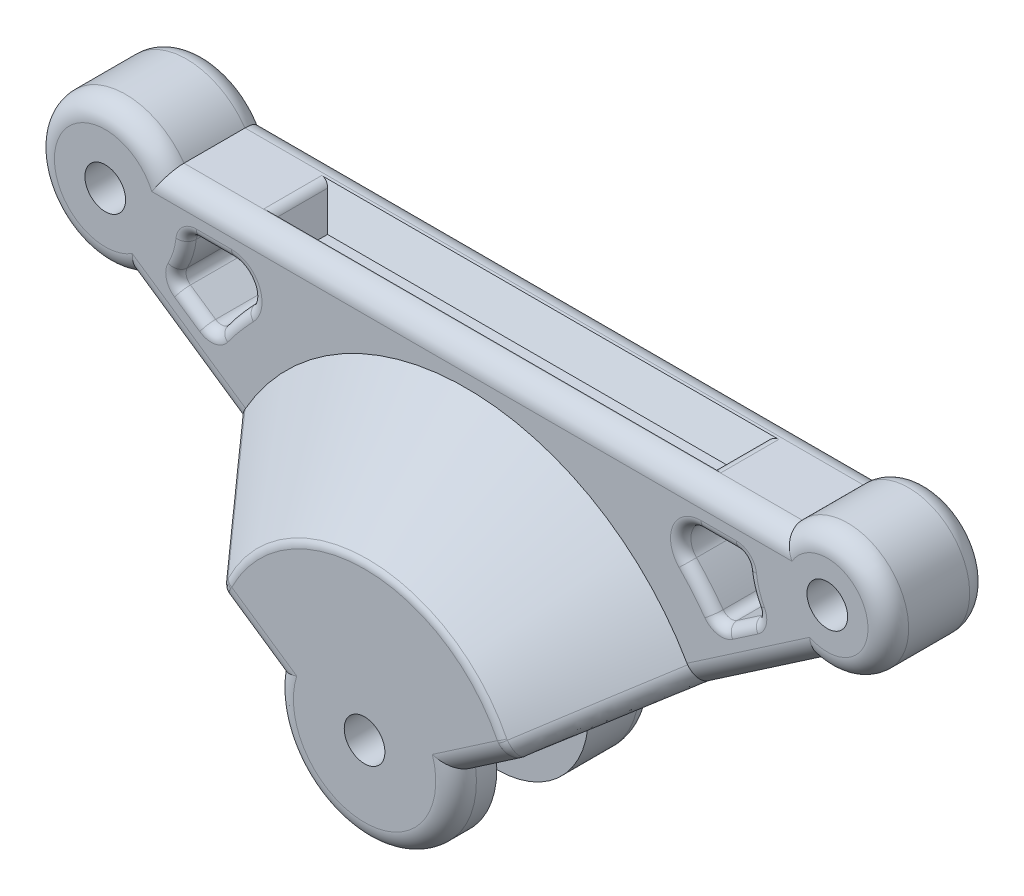
SolidWorks part; units mm, degrees
ref_plane "前视基准面" through (0, 0, 0) normal (0, 0, 1) x (1, 0, 0)
ref_plane "上视基准面" through (0, 0, 0) normal (0, 1, 0) x (1, 0, 0)
ref_plane "右视基准面" through (0, 0, 0) normal (1, 0, 0) x (0, 0, -1)
sketch "草图2" plane through (0, 0, 0) normal (0, 0, 1) x (1, 0, 0)
  line L0 (8.9132, 1.2471) -> (34.065, 18.4383)
  line L1 (31.0279, 28.2642) -> (-29.7554, 28.2642)
  line L2 (-33.0145, 17.7203) -> (-8.9132, 1.2471)
  arc A0 (-8.9132, 1.2471) -> (8.9132, 1.2471) centre (0, 0) ccw
  arc A1 (34.065, 18.4383) -> (31.0279, 28.2642) centre (35.5, 24.2642) ccw
  arc A2 (-29.7554, 28.2642) -> (-33.0145, 17.7203) centre (-35.5, 24.2642) ccw
  point P9 (-34.6477, 9.4763)
  point P10 (0, 0)
  dimension "D1" = 6
  dimension "D2" = 7
  dimension "D9" = 9
  dimension "D3" = 27.0171
  dimension "D4" = 60.7833
  dimension "D5" = 30.4656
  dimension "D6" = 29.1932
  dimension "D7" = 35.5
  dimension "D8" = 71
  dimension "D10" = 17.8264
extrude "凸台-拉伸1" add sketch "草图2" along normal blind 10
sketch "草图3" plane through (0, 0, 10) normal (0, 0, 1) x (1, 0, 0)
  line L0 (-8.9132, 1.2471) -> (-10.7168, 2.4799)
  line L1 (-33.0145, 17.7203) -> (-8.9132, 1.2471) construction
  line L2 (8.9132, 1.2471) -> (10.7168, 2.4799)
  line L3 (8.9132, 1.2471) -> (34.065, 18.4383) construction
  arc A0 (-8.9132, 1.2471) -> (8.9132, 1.2471) centre (0, 0) ccw construction
  arc A1 (-8.9132, 1.2471) -> (8.9132, 1.2471) centre (0, 0) ccw
  arc A2 (10.7168, 2.4799) -> (-10.7168, 2.4799) centre (0, 0) ccw
extrude "切除-拉伸1" cut sketch "草图3" against normal blind 3
sketch "草图4" plane through (0, 0, 10) normal (0, 0, 1) x (1, 0, 0)
  line L0 (10.7168, 2.4799) -> (34.065, 18.4383) construction
  line L1 (-33.0145, 17.7203) -> (-10.7168, 2.4799) construction
  line L2 (10.7168, 2.4799) -> (22.6308, 10.623)
  line L3 (-22.6308, 10.623) -> (-10.7168, 2.4799)
  arc A0 (22.6308, 10.623) -> (-22.6308, 10.623) centre (0, 0) ccw
  arc A1 (10.7168, 2.4799) -> (-10.7168, 2.4799) centre (0, 0) ccw construction
  arc A2 (10.7168, 2.4799) -> (-10.7168, 2.4799) centre (0, 0) ccw
extrude "凸台-拉伸2" add sketch "草图4" along normal blind 6
sketch "草图5" plane through (0, 0, 16) normal (0, 0, 1) x (1, 0, 0)
  line L0 (-10.7168, 2.4799) -> (-8.9132, 1.2471)
  line L1 (10.7168, 2.4799) -> (8.9132, 1.2471)
  line L2 (10.7168, 2.4799) -> (22.6308, 10.623)
  line L3 (-22.6308, 10.623) -> (-10.7168, 2.4799)
  line L4 (10.7168, 2.4799) -> (22.6308, 10.623)
  line L5 (-22.6308, 10.623) -> (-10.7168, 2.4799)
  arc A0 (-8.9132, 1.2471) -> (8.9132, 1.2471) centre (0, 0) ccw
  arc A2 (10.7168, 2.4799) -> (-10.7168, 2.4799) centre (0, 0) ccw
  arc A3 (22.6308, 10.623) -> (-22.6308, 10.623) centre (0, 0) ccw
  arc A5 (22.6308, 10.623) -> (-22.6308, 10.623) centre (0, 0) ccw
  dimension "D1" = 0
extrude "凸台-拉伸3" add sketch "草图5" along normal blind 4
sketch "草图6" plane through (0, 0, 0) normal (0, 0, -1) x (-1, 0, 0)
  line L0 (-28.8932, 19.7484) -> (-24.8254, 16.9681)
  line L1 (-23.0827, 24.2642) -> (-27.4968, 24.2642)
  line L2 (-31.0279, 28.2642) -> (29.7554, 28.2642) construction
  line L3 (-8.9132, 1.2471) -> (-34.065, 18.4383) construction
  line L4 (0.001, 0) -> (0.001, 28.2714) construction
  line L5 (23.0848, 24.2642) -> (27.4989, 24.2642)
  line L6 (28.8953, 19.7484) -> (24.8275, 16.9681)
  arc A0 (-24.8254, 16.9681) -> (-21.6432, 20.8757) centre (0.001, 0) cw
  arc A1 (-21.6432, 20.8757) -> (-23.0827, 24.2642) centre (-23.0827, 22.2642) ccw
  arc A2 (-27.4968, 24.2642) -> (-28.8932, 19.7484) centre (-35.4968, 24.2642) cw
  arc A3 (27.4989, 24.2642) -> (28.8953, 19.7484) centre (35.4989, 24.2642) ccw
  arc A4 (21.6453, 20.8757) -> (23.0848, 24.2642) centre (23.0848, 22.2642) cw
  arc A5 (24.8275, 16.9681) -> (21.6453, 20.8757) centre (0.001, 0) ccw
  dimension "D1" = 30.0711
  dimension "D2" = 2
  dimension "D3" = 8
  dimension "D6" = 12.73
  dimension "D4" = 4
  dimension "D5" = 4
  dimension "D7" = 15.9122
  dimension "D8" = 19.98
extrude "切除-拉伸2" cut sketch "草图6" against normal through all
draft "拔模1" type of draft neutral plane draft angle 45 faces to draft 1 face at (0, 17.8115, 15) neutral plane through (0, 0, 10) neutral plane normal (0, 0, 1) parameters "D1"=45
sketch "草图7" plane through (0, 28.2642, 0) normal (0, 1, 0) x (1, 0, 0)
  line L0 (-21.3644, -2.2763) -> (-21.3644, -7.9547)
  line L1 (-21.3644, -7.9547) -> (22.4255, -7.9547)
  line L2 (22.4255, -7.9547) -> (22.4255, -2.2763)
  line L3 (22.4255, -2.2763) -> (-21.3644, -2.2763)
extrude "切除-拉伸3" cut sketch "草图7" against normal blind 3 draft 30
sketch "草图8" plane through (0, 0, 0) normal (0, 0, -1) x (-1, 0, 0)
  circle A0 centre (0, 0) radius 2
  circle A5 centre (35.5, 24.2642) radius 2
  circle A6 centre (-35.5, 24.2642) radius 2
extrude "切除-拉伸4" cut sketch "草图8" against normal through all both and the other way through all
fillet "圆角1" radius 2 16 edges at (41.2324, 26.036, 0) (41.2324, 26.036, 10) (28.3479, 14.5307, 10) (11.5528, 3.0512, 20) (0, -9, 20) (-11.5528, 3.0512, 20) (-27.8226, 14.1716, 10) (-42.1878, 26.3314, 0) (-42.1878, 26.3314, 10) (0.6362, 28.2642, 10) (0.6362, 28.2642, 0) (0, -9, 0) (-20.9639, 9.4837, 0) (21.4891, 9.8427, 0)
fillet "圆角2" radius 1 5 edges at (13.9736, 5.4949, 19.4769) (-13.9736, 5.4949, 19.4769) (0, 15, 20)
fillet "圆角3" radius 1 28 edges at (27.8539, 21.9008, 0) (27.8539, 21.9008, 10) (26.8593, 18.3583, 0) (28.8932, 19.7484, 5) (26.8593, 18.3583, 10) (23.3163, 18.9887, 0) (24.8254, 16.9681, 5) (23.3163, 18.9887, 10) (-25.2919, 24.2642, 0) (-25.2919, 24.2642, 10) (-23.3184, 18.9887, 0) (-23.3184, 18.9887, 10) (-21.244, 23.0462, 0) (-21.244, 23.0462, 10) (-26.8614, 18.3583, 0) (-24.8275, 16.9681, 5) (-26.8614, 18.3583, 10) (-27.4989, 24.2642, 5) (-27.856, 21.9008, 0) (-28.8953, 19.7484, 5) (-27.856, 21.9008, 10) (21.242, 23.0462, 0) (21.242, 23.0462, 10) (27.4968, 24.2642, 5) (25.2898, 24.2642, 0) (25.2898, 24.2642, 10) (-21.3644, 28.2642, 5.1155) (22.4255, 28.2642, 5.1155)
